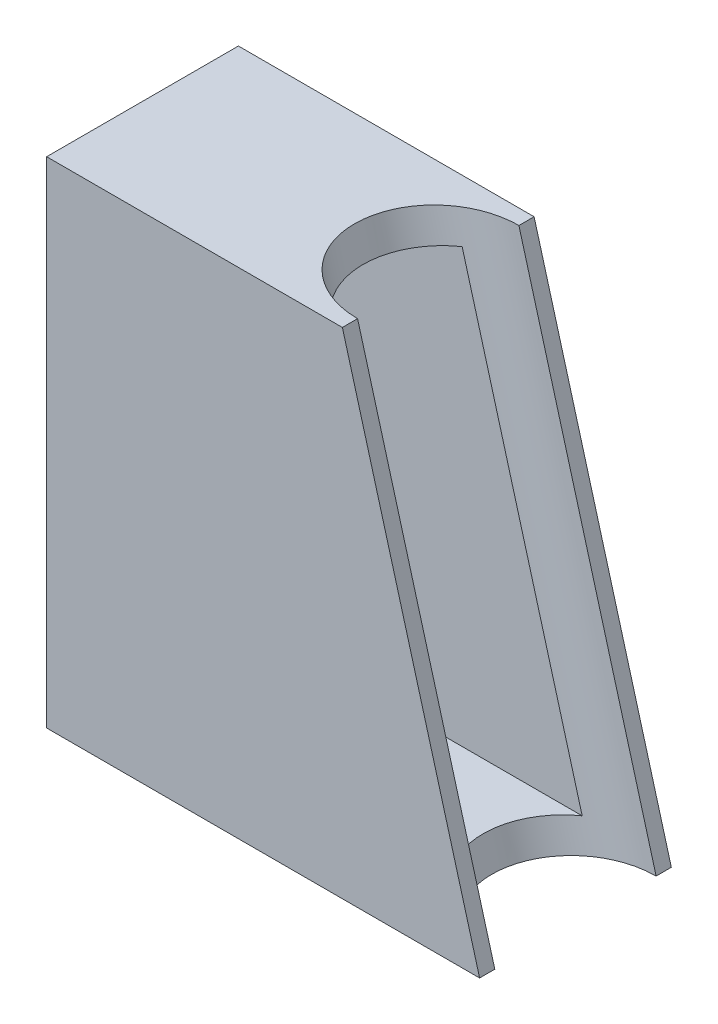
SolidWorks part; units mm, degrees
ref_plane "Front Plane" through (0, 0, 0) normal (0, 0, 1) x (1, 0, 0)
ref_plane "Top Plane" through (0, 0, 0) normal (0, 1, 0) x (1, 0, 0)
ref_plane "Right Plane" through (0, 0, 0) normal (1, 0, 0) x (0, 0, -1)
sketch "Sketch1" plane through (0, 0, 0) normal (0, 0, 1) x (1, 0, 0)
  line L0 (-75.5524, 34.0844) -> (-75.5524, -65.9156)
  line L1 (-5.5524, -65.9156) -> (-75.5524, -65.9156)
  line L2 (-5.5524, -65.9156) -> (-33.2874, 34.0844)
  line L3 (-33.2874, 34.0844) -> (-75.5524, 34.0844)
  dimension "D1" = 100
  dimension "D2" = 70
extrude "Boss-Extrude1" add sketch "Sketch1" along normal blind 31
sketch "Sketch5" plane through (-75.5524, 0, 0) normal (-1, 0, 0) x (0, 0, 1)
  line L0 (31, -65.9156) -> (0, -65.9156) construction
  line L1 (5, 9.0844) -> (26, 9.0844)
  line L2 (5, 9.0844) -> (5, -60.9156)
  line L3 (5, -60.9156) -> (26, -60.9156)
  line L4 (26, 9.0844) -> (26, -60.9156)
  line L5 (0, 34.0844) -> (0, -65.9156) construction
  line L6 (31, 34.0844) -> (0, 34.0844) construction
  line L7 (31, 34.0844) -> (31, -65.9156) construction
  dimension "D1" = 5
  dimension "D2" = 5
  dimension "D3" = 25
  dimension "D4" = 5
extrude "Cut-Extrude3" cut sketch "Sketch5" against normal blind 110
sketch "Sketch6" plane through (0, -60.9156, 0) normal (0, 1, 0) x (1, 0, 0)
  line L0 (-75.5524, -5) -> (-75.5524, -26) construction
  circle A0 centre (-60.5524, -14.6496) radius 6
  dimension "D1" = 12
  dimension "D2" = 15
extrude "Cut-Extrude4" cut sketch "Sketch6" against normal blind 110
sketch "Sketch7" plane through (-75.5524, 0, 0) normal (-1, 0, 0) x (0, 0, 1)
  line L0 (26, 9.0844) -> (5, 9.0844) construction
  line L1 (-21.0431, 14.0844) -> (61.833, 14.0844)
  line L2 (-21.0431, 14.0844) -> (-21.0431, 35.6433)
  line L3 (-21.0431, 35.6433) -> (61.833, 35.6433)
  line L4 (61.833, 14.0844) -> (61.833, 35.6433)
  dimension "D1" = 5
extrude "Cut-Extrude5" cut sketch "Sketch7" against normal blind 110
ref_plane "Plane1" through (-5.6088, 20.2226, 0) normal (-0.2673, 0.9636, 0) x (0.9636, 0.2673, 0)
sketch "Sketch8" plane through (-5.6088, 20.2226, 0) normal (-0.2673, 0.9636, 0) x (0.9636, 0.2673, 0)
  line L0 (-22.9671, 0) -> (-22.9671, -31) construction
  circle A0 centre (-22.9671, -15.5) radius 13.0414
extrude "Cut-Extrude6" cut sketch "Sketch8" against normal through all and the other way through all
